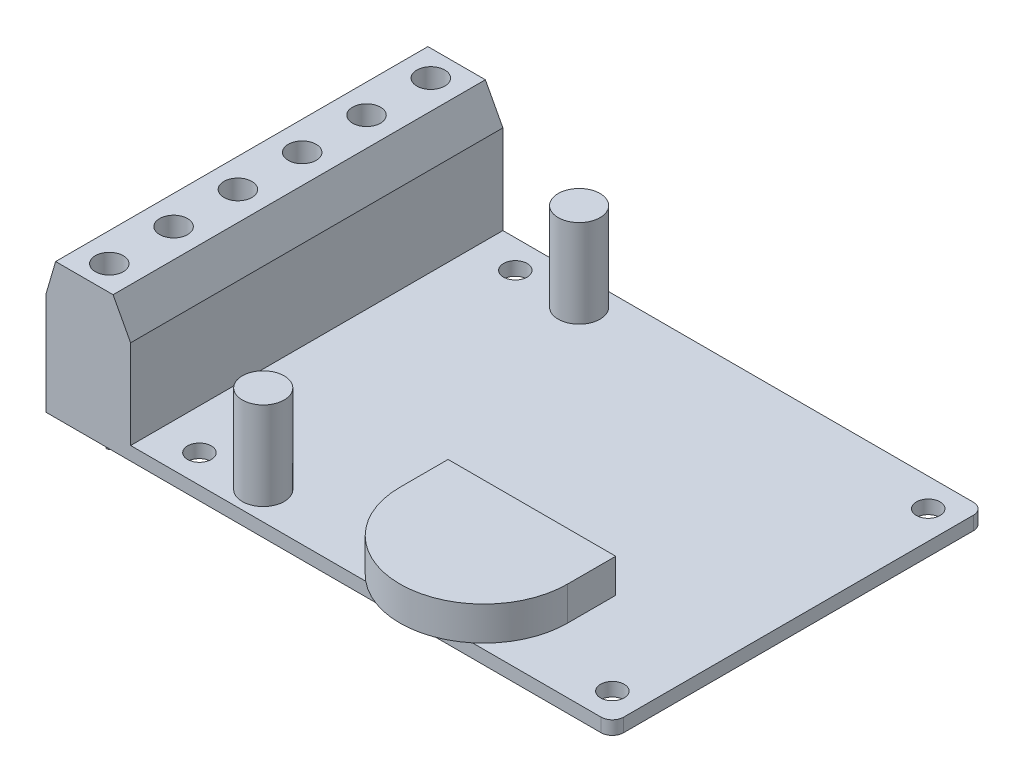
SolidWorks part; units mm, degrees
ref_plane "前视基准面" through (0, 0, 0) normal (0, 0, 1) x (1, 0, 0)
ref_plane "上视基准面" through (0, 0, 0) normal (0, 1, 0) x (1, 0, 0)
ref_plane "右视基准面" through (0, 0, 0) normal (1, 0, 0) x (0, 0, -1)
sketch "草图2" plane through (0, 0, 0) normal (0, 1, 0) x (1, 0, 0)
  line L0 (0, 0) -> (37.347, 0) construction
  line L1 (0, 0) -> (0, -35.97) construction
  line L3 (1, 0) -> (49.2, 0)
  line L4 (0, -1) -> (0, -32)
  line L5 (1, -33) -> (49.2, -33)
  line L6 (50.2, -1) -> (50.2, -32)
  arc A0 (1, 0) -> (0, -1) centre (1, -1) ccw
  arc A1 (0, -32) -> (1, -33) centre (1, -32) ccw
  arc A2 (49.2, -33) -> (50.2, -32) centre (49.2, -32) ccw
  arc A3 (49.2, 0) -> (50.2, -1) centre (49.2, -1) cw
  point P12 (0, -33)
  point P15 (50.2, -33)
  point P18 (50.2, 0)
  dimension "D3" = 1
  dimension "D1" = 50.2
  dimension "D2" = 33
extrude "凸台-拉伸1" add sketch "草图2" along normal blind 1.2
sketch "草图3" plane through (0, 0, 0) normal (0, 0, 1) x (1, 0, 0)
  line L0 (0, 0) -> (0, 9.0843)
  line L1 (0.8517, 12) -> (5.9459, 12)
  line L2 (7.5, 9.0843) -> (7.5, 0)
  line L3 (1, 0) -> (49.2, 0) construction
  line L4 (0.8517, 12) -> (0, 9.0843)
  line L5 (3.75, 12) -> (3.75, -2.4652) construction
  line L6 (5.9459, 12) -> (7.5, 9.0843)
  line L7 (7.5, 0) -> (0, 0)
  dimension "D1" = 12
  dimension "D2" = 7.5
extrude "凸台-拉伸3" add sketch "草图3" along normal blind 33 separate body
sketch "草图4" plane through (0, 12, 0) normal (0, 1, 0) x (1, 0, 0)
  line L0 (0.8517, -16.5) -> (38.1743, -16.5) construction
  line L1 (0.8517, -33) -> (0.8517, 0) construction
  line L2 (3.3988, 0) -> (3.3988, -35.8947) construction
  line L3 (5.9459, 0) -> (0.8517, 0) construction
  circle A0 centre (3.3988, -2.2884) radius 1.238
  circle A1 centre (3.3988, -7.9884) radius 1.238
  circle A2 centre (3.3988, -13.6884) radius 1.238
  circle A3 centre (3.3988, -19.3884) radius 1.238
  circle A4 centre (3.3988, -25.0884) radius 1.238
  circle A5 centre (3.3988, -30.7884) radius 1.238
  dimension "D1" = 6
extrude "切除-拉伸1" cut sketch "草图4" against normal blind 2
sketch "草图5" plane through (0, 1.2, 0) normal (0, 1, 0) x (1, 0, 0)
  line L0 (50.2, -32) -> (50.2, -1) construction
  line L1 (49.2, 0) -> (1, 0) construction
  line L2 (50.2, -16.5) -> (22.4036, -16.5) construction
  circle A0 centre (47.7, -2.5) radius 1.05
  circle A1 centre (47.7, -30.5) radius 1.05
  circle A2 centre (11.1, -2.5) radius 1.05
  circle A3 centre (11.1, -30.5) radius 1.05
  dimension "D1" = 2.1
  dimension "D2" = 2.5
  dimension "D3" = 2.5
  dimension "D5" = 36.6
  dimension "D4" = 2
extrude "切除-拉伸2" cut sketch "草图5" against normal blind 2
sketch "草图6" plane through (0, 0, 0) normal (0, -1, 0) x (1, 0, 0)
  circle A12 centre (3.3988, 25.0884) radius 0.4351
  circle A13 centre (3.3988, 19.3884) radius 0.4351
  circle A14 centre (3.3988, 13.6884) radius 0.4351
  circle A15 centre (3.3988, 7.9884) radius 0.4351
  circle A16 centre (3.3988, 2.2884) radius 0.4351
  circle A17 centre (3.3988, 30.7884) radius 0.4351
extrude "凸台-拉伸4" add sketch "草图6" along normal blind 0.1
sketch "草图7" plane through (0, -0.1, 0) normal (0, -1, 0) x (1, 0, 0)
  circle A0 centre (3.3988, 30.7884) radius 0.2215
  circle A1 centre (3.3988, 25.0884) radius 0.2215
  circle A2 centre (3.3988, 19.3884) radius 0.2215
  circle A3 centre (3.3988, 13.6884) radius 0.2215
  circle A4 centre (3.3988, 7.9884) radius 0.2215
  circle A5 centre (3.3988, 2.2884) radius 0.2215
extrude "凸台-拉伸5" add sketch "草图7" along normal blind 2
sketch "草图8" plane through (0, 0, 0) normal (0, -1, 0) x (1, 0, 0)
  line L0 (18.0643, 16.5) -> (35.5172, 16.5) construction
  text T0 "Ruige"
extrude "凸台-拉伸6" add sketch "草图8" along normal blind 0.01
sketch "草图9" plane through (0, 1.2, 0) normal (0, 1, 0) x (1, 0, 0)
  line L0 (50.2, -16.5) -> (5.4837, -16.5) construction
  line L1 (50.2, -32) -> (50.2, -1) construction
sketch "草图10" plane through (0, 1.2, 0) normal (0, 1, 0) x (1, 0, 0)
  line L0 (16.7553, -16.5) -> (16.7553, -1.0833) construction
  line L1 (50.2, -16.5) -> (5.4837, -16.5) construction
  line L2 (16.7553, -16.5) -> (24.7546, -16.5) construction
  circle A0 centre (16.7553, -2.5) radius 1.8546
  circle A1 centre (16.7553, -30.5) radius 1.8546
extrude "凸台-拉伸7" add sketch "草图10" along normal blind 7.8
sketch "草图11" plane through (0, 1.2, 0) normal (0, 1, 0) x (1, 0, 0)
  line L0 (25.64, -23) -> (40.5, -23)
  line L1 (40.5, -23) -> (40.5, -27.27)
  line L2 (25.64, -23) -> (25.64, -27.27)
  line L3 (25.64, -27.27) -> (33.07, -27.27) construction
  line L4 (7.5, -33) -> (49.2, -33) construction
  line L5 (50.2, -32) -> (50.2, -1) construction
  arc A0 (25.64, -27.27) -> (40.5, -27.27) centre (33.07, -27.27) ccw
  dimension "D1" = 10
  dimension "D2" = 7.43
  dimension "D3" = 4.27
  dimension "D4" = 9.7
extrude "凸台-拉伸8" add sketch "草图11" along normal blind 3
